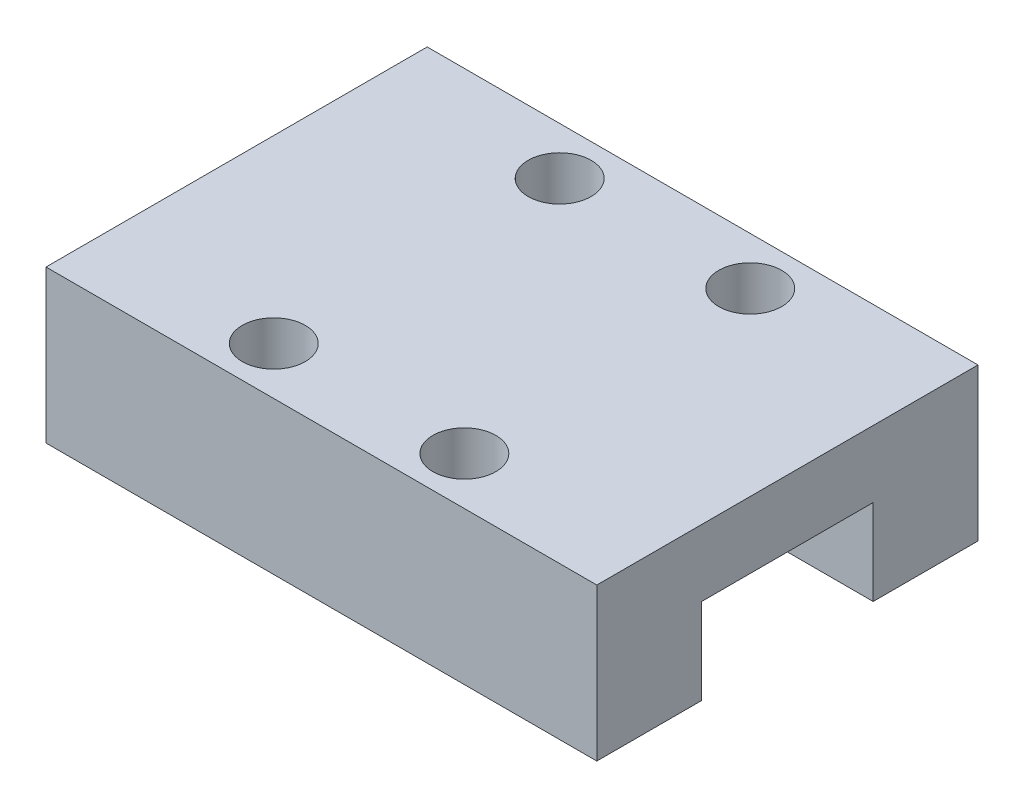
SolidWorks part; units mm, degrees
ref_plane "Front Plane" through (0, 0, 0) normal (0, 0, 1) x (1, 0, 0)
ref_plane "Top Plane" through (0, 0, 0) normal (0, 1, 0) x (1, 0, 0)
ref_plane "Right Plane" through (0, 0, 0) normal (1, 0, 0) x (0, 0, -1)
sketch "Sketch1" plane through (0, 0, 0) normal (1, 0, 0) x (0, 0, -1)
  line L0 (0, 0) -> (10, 0)
  line L1 (10, 0) -> (10, -8)
  line L2 (10, -8) -> (4.5, -8)
  line L3 (4.5, -8) -> (4.5, -3.5)
  line L4 (4.5, -3.5) -> (-4.5, -3.5)
  line L5 (-4.5, -3.5) -> (-4.5, -8)
  line L6 (-4.5, -8) -> (-10, -8)
  line L7 (-10, -8) -> (-10, 0)
  line L8 (-10, 0) -> (0, 0)
  dimension "D1" = 20
  dimension "D2" = 8
  dimension "D3" = 9
  dimension "D4" = 4.5
extrude "Boss-Extrude1" add sketch "Sketch1" along normal mid plane 28.9
sketch "Sketch2" plane through (0, 0, 0) normal (0, 1, 0) x (1, 0, 0)
  line L1 (-5, 7.5) -> (5, 7.5) construction
  line L2 (-5, 7.5) -> (-5, -7.5) construction
  line L3 (-5, -7.5) -> (5, -7.5) construction
  line L4 (5, 7.5) -> (5, -7.5) construction
  line L5 (-5, 7.5) -> (5, -7.5) construction
  line L6 (-5, -7.5) -> (5, 7.5) construction
  circle A0 centre (5, 7.5) radius 1.651
  circle A1 centre (5, -7.5) radius 1.651
  circle A2 centre (-5, -7.5) radius 1.651
  circle A3 centre (-5, 7.5) radius 1.651
  point P0 (0, 0)
  dimension "D3" = 3.302
  dimension "D1" = 10
  dimension "D2" = 15
extrude "Cut-Extrude1" cut sketch "Sketch2" against normal blind 6.35
